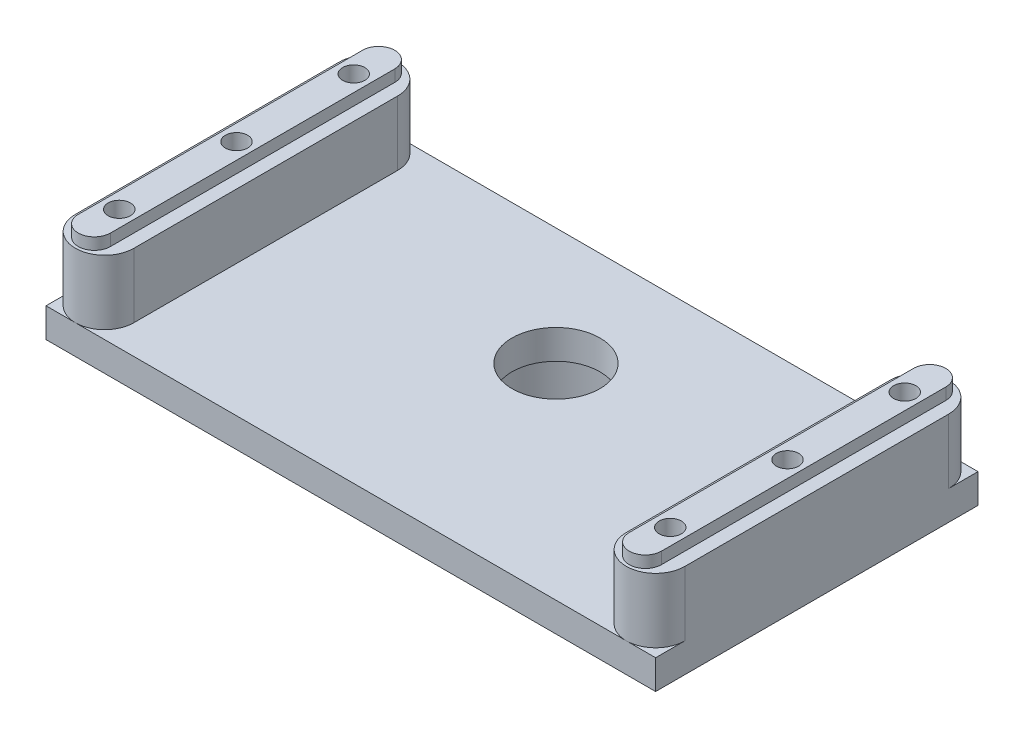
SolidWorks part; units mm, degrees
ref_plane "Front" through (0, 0, 0) normal (0, 0, 1) x (1, 0, 0)
ref_plane "Top" through (0, 0, 0) normal (0, 1, 0) x (1, 0, 0)
ref_plane "Right" through (0, 0, 0) normal (1, 0, 0) x (0, 0, -1)
sketch "Sketch1" plane through (0, 0, 0) normal (0, 1, 0) x (1, 0, 0)
  line L1 (-52, -27.5) -> (52, -27.5)
  line L2 (-52, -27.5) -> (-52, 27.5)
  line L3 (-52, 27.5) -> (52, 27.5)
  line L4 (52, -27.5) -> (52, 27.5)
  line L5 (-52, -27.5) -> (52, 27.5) construction
  line L6 (-52, 27.5) -> (52, -27.5) construction
  point P0 (0, 0)
  dimension "D1" = 104
  dimension "D2" = 55
extrude "Boss-Extrude1" add sketch "Sketch1" along normal blind 5
sketch "Sketch2" plane through (0, 5, 0) normal (0, 1, 0) x (1, 0, 0)
  line L0 (-47, -22.5) -> (-47, 22.5) construction
  line L1 (-52, -22.5) -> (-52, 22.5)
  line L2 (-42, -22.5) -> (-42, 22.5)
  line L3 (47, -22.5) -> (47, 22.5) construction
  line L4 (42, -22.5) -> (42, 22.5)
  line L5 (52, -22.5) -> (52, 22.5)
  line L9 (52, 27.5) -> (-52, 27.5) construction
  arc A0 (-52, -22.5) -> (-42, -22.5) centre (-47, -22.5) ccw
  arc A1 (-42, 22.5) -> (-52, 22.5) centre (-47, 22.5) ccw
  arc A2 (42, -22.5) -> (52, -22.5) centre (47, -22.5) ccw
  arc A3 (52, 22.5) -> (42, 22.5) centre (47, 22.5) ccw
  point P2 (-47, 0)
  point P11 (47, 0)
  dimension "D1" = 47
  dimension "D2" = 10
  dimension "D3" = 45
  dimension "D4" = 47
  dimension "D5" = 10
  dimension "D6" = 45
  dimension "D7" = 27.5
  dimension "D8" = 27.5
extrude "Boss-Extrude2" add sketch "Sketch2" along normal blind 11
sketch "Sketch3" plane through (0, 16, 0) normal (0, 1, 0) x (1, 0, 0)
  line L0 (-47, -24.25) -> (-47, 24.25) construction
  line L1 (-49.75, -24.25) -> (-49.75, 24.25)
  line L2 (-44.25, -24.25) -> (-44.25, 24.25)
  line L3 (47, -24.25) -> (47, 24.25) construction
  line L4 (44.25, -24.25) -> (44.25, 24.25)
  line L5 (49.75, -24.25) -> (49.75, 24.25)
  line L6 (-52, 22.5) -> (-52, -22.5) construction
  arc A0 (-49.75, -24.25) -> (-44.25, -24.25) centre (-47, -24.25) ccw
  arc A1 (-44.25, 24.25) -> (-49.75, 24.25) centre (-47, 24.25) ccw
  arc A2 (44.25, -24.25) -> (49.75, -24.25) centre (47, -24.25) ccw
  arc A3 (49.75, 24.25) -> (44.25, 24.25) centre (47, 24.25) ccw
  point P2 (-47, 0)
  point P11 (47, 0)
  dimension "D1" = 5
  dimension "D2" = 5.5
  dimension "D3" = 48.5
  dimension "D4" = 2
extrude "Boss-Extrude3" add sketch "Sketch3" along normal blind 2
sketch "Sketch4" plane through (0, 18, 0) normal (0, 1, 0) x (1, 0, 0)
  circle A0 centre (-47, 0) radius 1.9
  circle A1 centre (-47, 20) radius 1.9
  circle A2 centre (-47, -20) radius 1.9
  circle A3 centre (47, 0) radius 1.9
  circle A4 centre (47, 20) radius 1.9
  circle A5 centre (47, -20) radius 1.9
  dimension "D1" = 3.8
  dimension "D2" = 47
  dimension "D3" = 2
  dimension "D4" = 2
  dimension "D5" = 2
extrude "Cut-Extrude1" cut sketch "Sketch4" against normal blind 23
sketch "Sketch5" plane through (0, 0, 0) normal (0, -1, 0) x (1, 0, 0)
  line L6 (47, -27.5) -> (-47, -27.5) construction
  circle A0 centre (-47, 0) radius 1.9 construction
  circle A1 centre (0, -7.5) radius 17.25
  circle A6 centre (0, -7.5) radius 12.75
  point P17 (0, -7.5)
  point P19 (0, -7.5)
  dimension "D3" = 47
  dimension "D7" = 25.5
  dimension "D1" = 34.5
  dimension "D2" = 20
extrude "Boss-Extrude4" add sketch "Sketch5" along normal blind 10
sketch "Sketch7" plane through (0, -10, 0) normal (0, -1, 0) x (1, 0, 0)
  circle A0 centre (0, -7.5) radius 7.5
  point P14 (0, -7.5)
  dimension "D1" = 15
extrude "Cut-Extrude2" cut sketch "Sketch7" against normal blind 35
